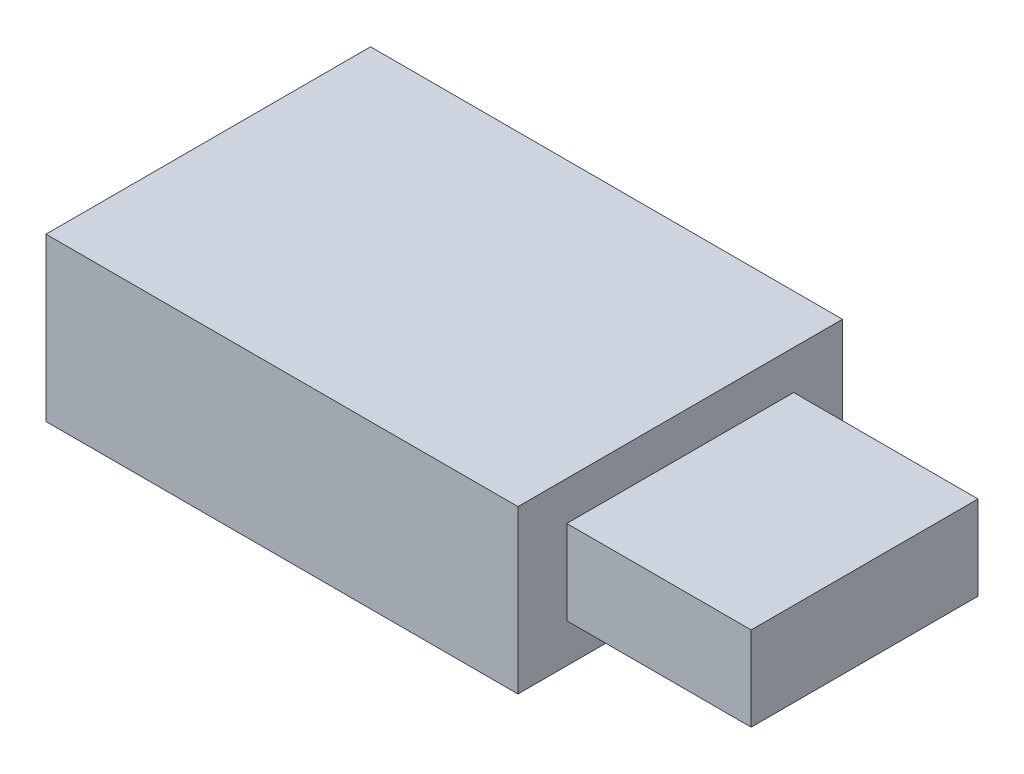
SolidWorks part; units mm, degrees
ref_plane "Front Plane" through (0, 0, 0) normal (0, 0, 1) x (1, 0, 0)
ref_plane "Top Plane" through (0, 0, 0) normal (0, 1, 0) x (1, 0, 0)
ref_plane "Right Plane" through (0, 0, 0) normal (1, 0, 0) x (0, 0, -1)
sketch "Sketch1" plane through (0, 0, 0) normal (0, 1, 0) x (1, 0, 0)
  line L0 (12.4841, 0) -> (0, 0) construction
  line L1 (-12.4841, -8.5852) -> (12.4841, -8.5852)
  line L2 (-12.4841, -8.5852) -> (-12.4841, 8.5852)
  line L3 (-12.4841, 8.5852) -> (12.4841, 8.5852)
  line L4 (12.4841, -8.5852) -> (12.4841, 8.5852)
  line L5 (0, 8.5852) -> (0, 0) construction
  dimension "D1" = 24.9682
  dimension "D2" = 17.1704
extrude "Boss-Extrude1" add sketch "Sketch1" along normal mid plane 8.5852
sketch "Sketch3" plane through (12.4841, 0, 0) normal (1, 0, 0) x (0, 0, -1)
  line L1 (-6.0008, -2.2288) -> (6.0007, -2.2288)
  line L2 (-6.0008, -2.2288) -> (-6.0008, 2.2288)
  line L3 (-6.0008, 2.2288) -> (6.0007, 2.2288)
  line L4 (6.0007, -2.2288) -> (6.0007, 2.2288)
  line L5 (-6.0008, -2.2288) -> (6.0007, 2.2288) construction
  line L6 (-6.0008, 2.2288) -> (6.0007, -2.2288) construction
  point P0 (0, 0)
  dimension "D1" = 12.0015
  dimension "D2" = 4.4577
extrude "Boss-Extrude2" add sketch "Sketch3" along normal blind 9.7536
sketch "Sketch4" plane through (-12.4841, 0, 0) normal (-1, 0, 0) x (0, 0, 1)
  circle A0 centre (0, 0) radius 1.27
extrude "Boss-Extrude3" add sketch "Sketch4" along normal blind 2.54
